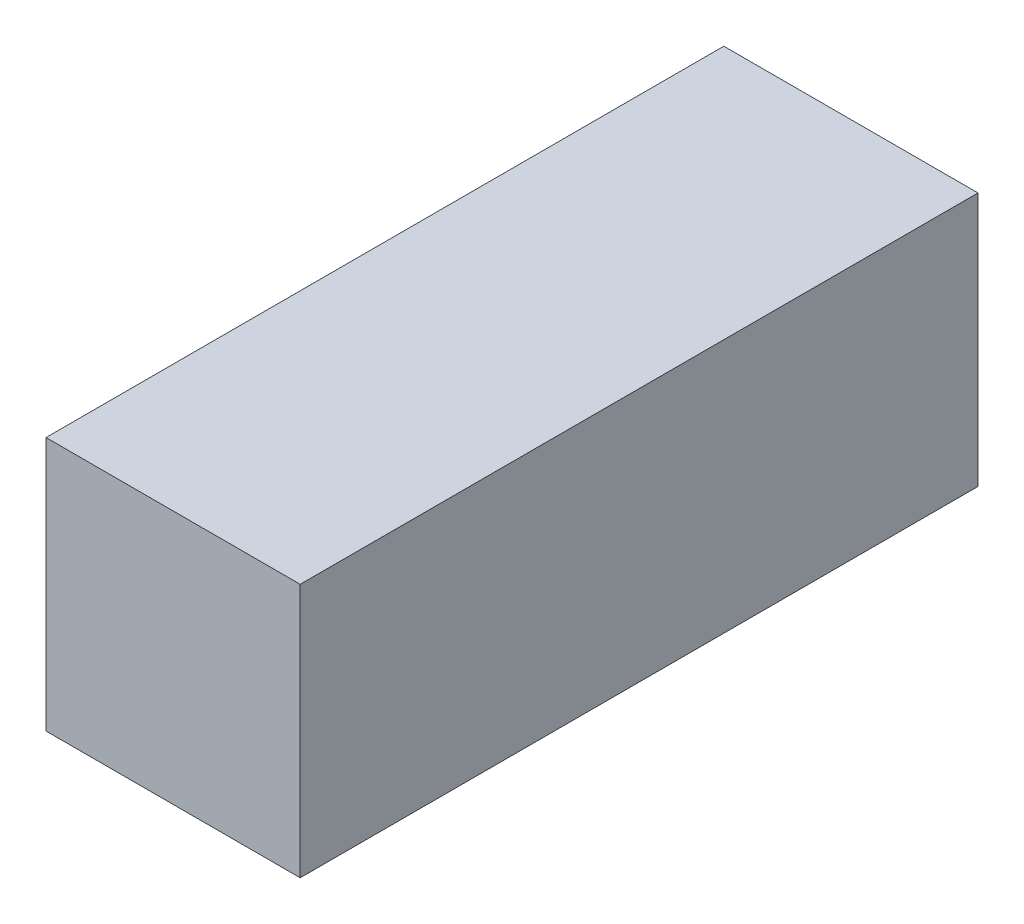
SolidWorks part; units mm, degrees
ref_plane "Front Plane" through (0, 0, 0) normal (0, 0, 1) x (1, 0, 0)
ref_plane "Top Plane" through (0, 0, 0) normal (0, 1, 0) x (1, 0, 0)
ref_plane "Right Plane" through (0, 0, 0) normal (1, 0, 0) x (0, 0, -1)
sketch "Sketch1" plane through (0, 0, 0) normal (0, 0, 1) x (1, 0, 0)
  line L1 (0, 0) -> (38.1, 0)
  line L2 (0, 0) -> (0, 38.1)
  line L3 (0, 38.1) -> (38.1, 38.1)
  line L4 (38.1, 0) -> (38.1, 38.1)
  dimension "D1" = 38.1
extrude "Boss-Extrude1" add sketch "Sketch1" along normal blind 101.6
